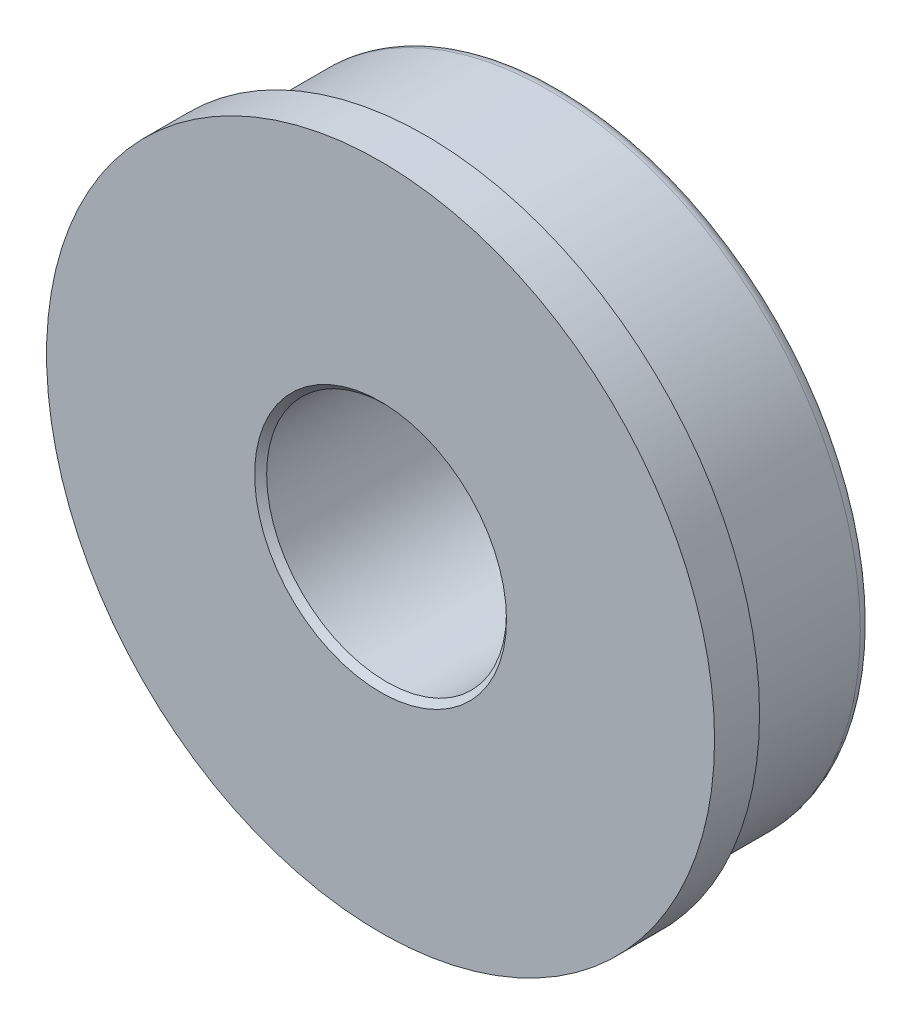
SolidWorks part; units mm, degrees
ref_plane "前视基准面" through (0, 0, 0) normal (0, 0, 1) x (1, 0, 0)
ref_plane "上视基准面" through (0, 0, 0) normal (0, 1, 0) x (1, 0, 0)
ref_plane "右视基准面" through (0, 0, 0) normal (1, 0, 0) x (0, 0, -1)
sketch "草图1" plane through (0, 0, 0) normal (0, 0, 1) x (1, 0, 0)
  circle A0 centre (0, 0) radius 26
  circle A1 centre (0, 0) radius 10
  dimension "D1" = 20
  dimension "D2" = 52
extrude "凸台-拉伸1" add sketch "草图1" along normal mid plane 15
sketch "草图2" plane through (0, 0, 7.5) normal (0, 0, 1) x (1, 0, 0)
  circle A0 centre (0, 0) radius 27.85
  circle A1 centre (0, 0) radius 26 construction
  circle A2 centre (0, 0) radius 26
  dimension "D1" = 55.7
extrude "凸台-拉伸2" add sketch "草图2" against normal blind 3.75
chamfer "倒角1" distance 0.5 angle 45 2 edges at (10, 0, -7.5) (10, 0, 7.5)
fillet "圆角1" radius 1 1 edges at (26, 0, -7.5)
